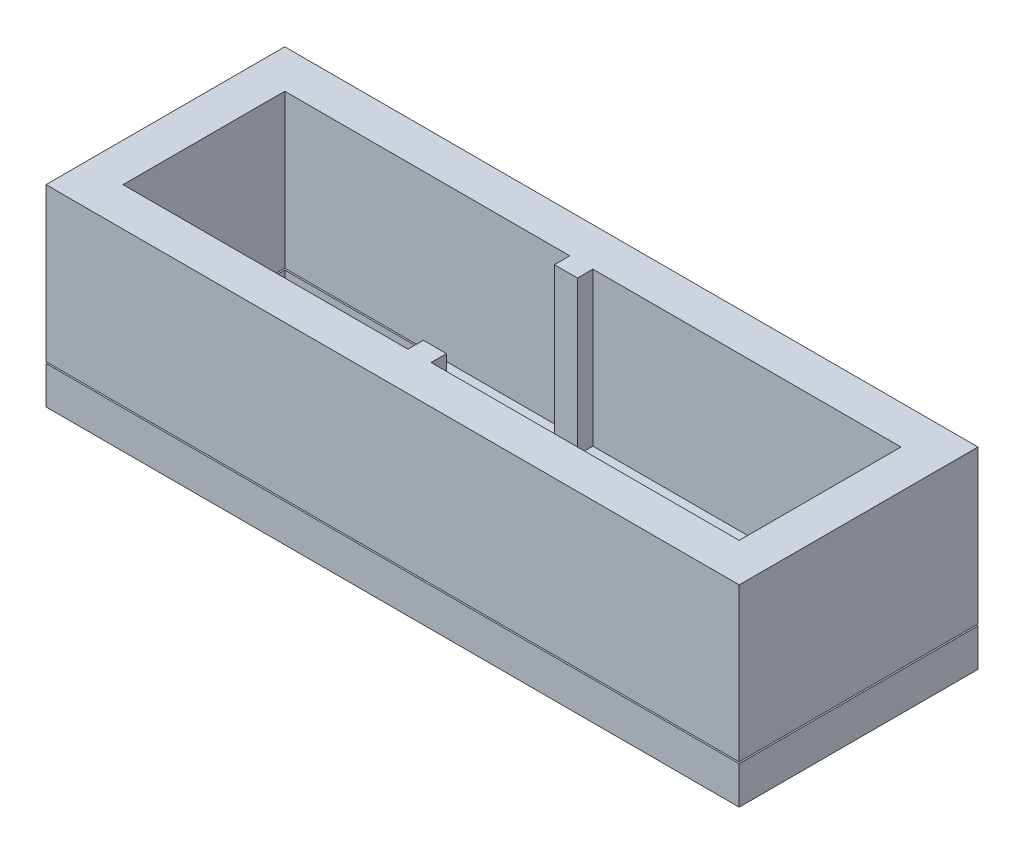
SolidWorks part; units mm, degrees
ref_plane "Front Plane" through (0, 0, 0) normal (0, 0, 1) x (1, 0, 0)
ref_plane "Top Plane" through (0, 0, 0) normal (0, 1, 0) x (1, 0, 0)
ref_plane "Right Plane" through (0, 0, 0) normal (1, 0, 0) x (0, 0, -1)
sketch "Sketch1" plane through (0, 0, 0) normal (0, 1, 0) x (1, 0, 0)
  line L1 (-50.8, -13.335) -> (50.8, -13.335)
  line L2 (-50.8, -13.335) -> (-50.8, 13.335)
  line L3 (-50.8, 13.335) -> (50.8, 13.335)
  line L4 (50.8, -13.335) -> (50.8, 13.335)
  line L5 (-50.8, -13.335) -> (50.8, 13.335) construction
  line L6 (-50.8, 13.335) -> (50.8, -13.335) construction
  line L7 (-57.15, -19.685) -> (57.15, -19.685)
  line L8 (-57.15, -19.685) -> (-57.15, 19.685)
  line L9 (-57.15, 19.685) -> (57.15, 19.685)
  line L10 (57.15, -19.685) -> (57.15, 19.685)
  line L11 (-57.15, -19.685) -> (57.15, 19.685) construction
  line L12 (-57.15, 19.685) -> (57.15, -19.685) construction
  point P0 (0, 0)
  point P6 (0, 0)
  dimension "D1" = 101.6
  dimension "D2" = 26.67
  dimension "D3" = 6.35
  dimension "D4" = 6.35
extrude "Boss-Extrude1" add sketch "Sketch1" along normal blind 25.4
sketch "Sketch3" plane through (0, 0, 0) normal (0, -1, 0) x (1, 0, 0)
  line L4 (57.15, -19.685) -> (57.15, 19.685)
  line L5 (57.15, 19.685) -> (-57.15, 19.685)
  line L6 (-57.15, 19.685) -> (-57.15, -19.685)
  line L7 (-57.15, -19.685) -> (57.15, -19.685)
  line L8 (57.15, -19.685) -> (57.15, 19.685)
  line L9 (57.15, 19.685) -> (-57.15, 19.685)
  line L10 (-57.15, 19.685) -> (-57.15, -19.685)
  line L11 (-57.15, -19.685) -> (57.15, -19.685)
  dimension "D1" = 0
extrude "Boss-Extrude2" add sketch "Sketch3" along normal blind 6.35
sketch "Sketch4" plane through (0, 0, 0) normal (0, 1, 0) x (1, 0, 0)
  line L0 (0, -13.335) -> (0, 13.335) construction
  line L1 (-50.8, -13.335) -> (50.8, -13.335) construction
  line L2 (50.8, 13.335) -> (-50.8, 13.335) construction
  line L3 (-50.8, 0) -> (50.8, 0) construction
  line L4 (0, -13.335) -> (-3.81, -13.335)
  line L5 (0, -13.335) -> (0, -10.795)
  line L6 (0, -10.795) -> (-3.81, -10.795)
  line L7 (-3.81, -13.335) -> (-3.81, -10.795)
  line L8 (-50.8, 13.335) -> (-50.8, -13.335) construction
  line L9 (50.8, -13.335) -> (50.8, 13.335) construction
  line L10 (-3.81, 13.335) -> (-3.81, 10.795)
  line L11 (0, 13.335) -> (-3.81, 13.335)
  line L12 (0, 13.335) -> (0, 10.795)
  line L13 (0, 10.795) -> (-3.81, 10.795)
  dimension "D1" = 2.54
  dimension "D2" = 3.81
extrude "Boss-Extrude3" add sketch "Sketch4" along normal blind 25.4
sketch "Sketch8" plane through (0, 0, 0) normal (0, 1, 0) x (1, 0, 0)
  line L0 (-50.8, -13.335) -> (-3.81, -13.335) construction
  line L1 (-50.8, 13.335) -> (-24.13, 13.335)
  line L2 (-50.8, 13.335) -> (-50.8, -13.335)
  line L3 (-50.8, -13.335) -> (-24.13, -13.335)
  line L4 (-24.13, 13.335) -> (-24.13, -13.335)
  dimension "D1" = 26.67
extrude "Cut-Extrude2" cut sketch "Sketch8" against normal blind 19.05
sketch "Sketch7" plane through (0, 0, 19.685) normal (0, 0, 1) x (1, 0, 0)
  line L0 (0, 0) -> (57.15, 0)
  line L1 (57.15, 25.4) -> (57.15, -6.35) construction
  line L2 (0, 0) -> (-57.15, 0)
  line L3 (-57.15, 25.4) -> (-57.15, -6.35) construction
extrude "Cut-Extrude-Thin1" cut sketch "Sketch7" against normal through all and the other way through all thin thin type mid plane wall 0.254
